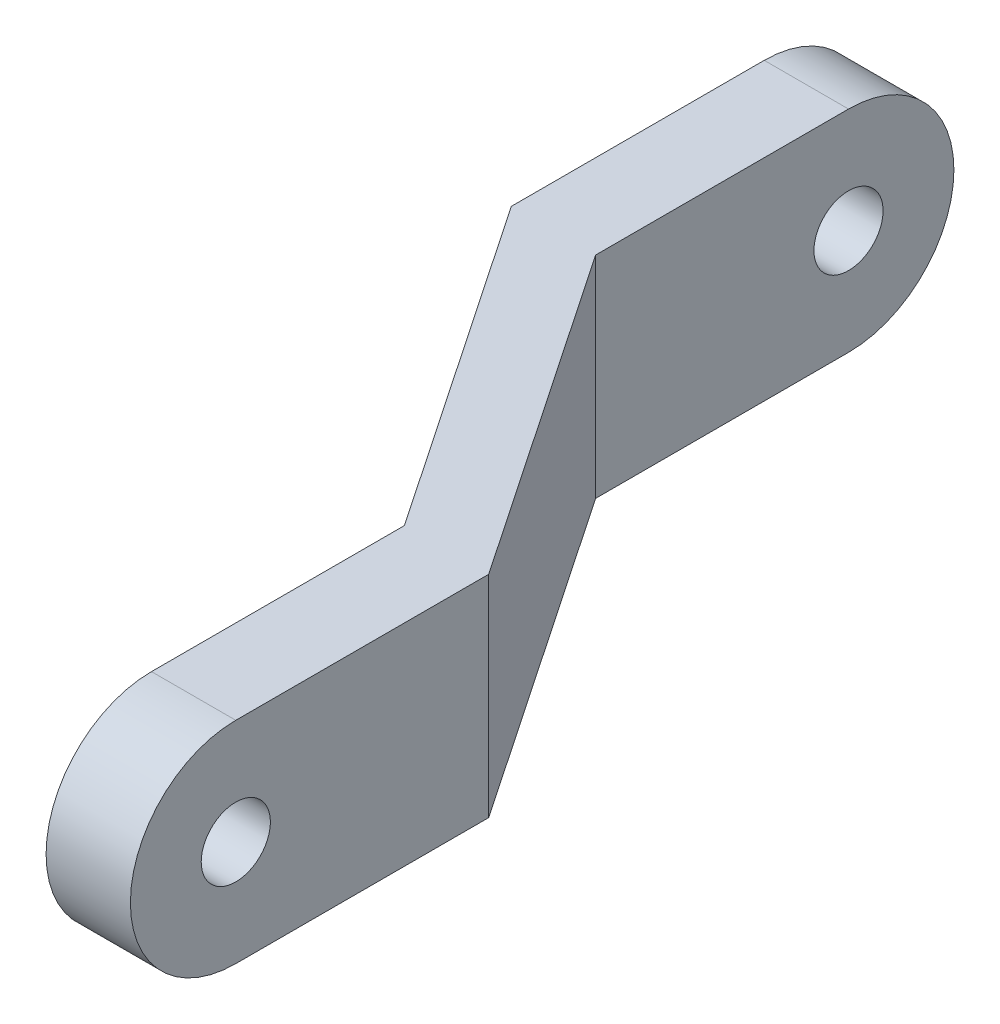
SolidWorks part; units mm, degrees
material "Custom Plastic"
ref_plane "Front Plane" through (0, 0, 0) normal (0, 0, 1) x (1, 0, 0)
ref_plane "Top Plane" through (0, 0, 0) normal (0, 1, 0) x (1, 0, 0)
ref_plane "Right Plane" through (0, 0, 0) normal (1, 0, 0) x (0, 0, -1)
sketch "Sketch1" plane through (0, 0, 0) normal (0, 1, 0) x (1, 0, 0)
  line L1 (-16.6817, -25.1794) -> (-16.6817, 0) construction
  line L2 (-16.6817, -23.966) -> (-16.6817, -26.2833) construction
  line L3 (-16.6817, -25.1794) -> (-16.6817, -17.5594)
  line L8 (-25.9404, 0) -> (-25.9404, -7.62)
  line L9 (-25.9404, -7.62) -> (-19.2217, -17.5594)
  line L10 (-19.2217, -25.1794) -> (-19.2217, -17.5594)
  line L11 (-23.4004, 0) -> (-23.4004, -7.62)
  line L12 (-23.4004, -7.62) -> (-16.6817, -17.5594)
  line L13 (-25.9404, 0) -> (-25.9404, 3.175)
  line L14 (-25.9404, 3.175) -> (-23.4004, 3.175)
  line L15 (-23.4004, 3.175) -> (-23.4004, 0)
  line L16 (-19.2217, -25.1794) -> (-19.2217, -28.3544)
  line L17 (-19.2217, -28.3544) -> (-16.6817, -28.3544)
  line L18 (-16.6817, -21.5505) -> (-16.6817, -28.8083) construction
  line L19 (-16.6817, -28.3544) -> (-16.6817, -25.1794)
  arc A0 (-22.5007, 6.35) -> (-22.5007, -6.35) centre (-0.5404, 0) ccw construction
extrude "Boss-Extrude1" add sketch "Sketch1" along normal blind 6.35
sketch "Sketch2" plane through (-25.9404, 0, 0) normal (-1, 0, 0) x (0, 0, 1)
  line L1 (-3.175, 6.35) -> (7.62, 6.35) construction
  line L2 (0, 10.5501) -> (0, 4.8351) construction
  line L3 (-3.175, 0) -> (7.62, 0) construction
  circle A0 centre (0, 3.175) radius 1.0414
  arc A1 (0, 6.35) -> (0, 0) centre (0, 3.175) ccw
  line M2 (-3.175, 0) -> (7.62, 0)
  line M4 (7.62, 6.35) -> (-3.175, 6.35)
  line M5 (-3.175, 6.35) -> (-3.175, 0)
extrude "Cut-Extrude1" cut sketch "Sketch2" against normal through all contours A1 M4 M5 | A1 M5 M2 | A0
sketch "Sketch3" plane through (-19.2217, 0, 0) normal (-1, 0, 0) x (0, 0, 1)
  line L1 (17.5594, 6.35) -> (28.3544, 6.35) construction
  line L2 (17.5594, 0) -> (28.3544, 0) construction
  circle A0 centre (25.1794, 3.175) radius 1.0414
  arc A1 (25.1794, 6.35) -> (25.1794, 0) centre (25.1794, 3.175) cw
  line M1 (17.5594, 0) -> (28.3544, 0)
  line M2 (28.3544, 0) -> (28.3544, 6.35)
  line M3 (28.3544, 6.35) -> (17.5594, 6.35)
extrude "Cut-Extrude2" cut sketch "Sketch3" against normal through all contours A1 M3 M2 | A1 M2 M1 | A0
